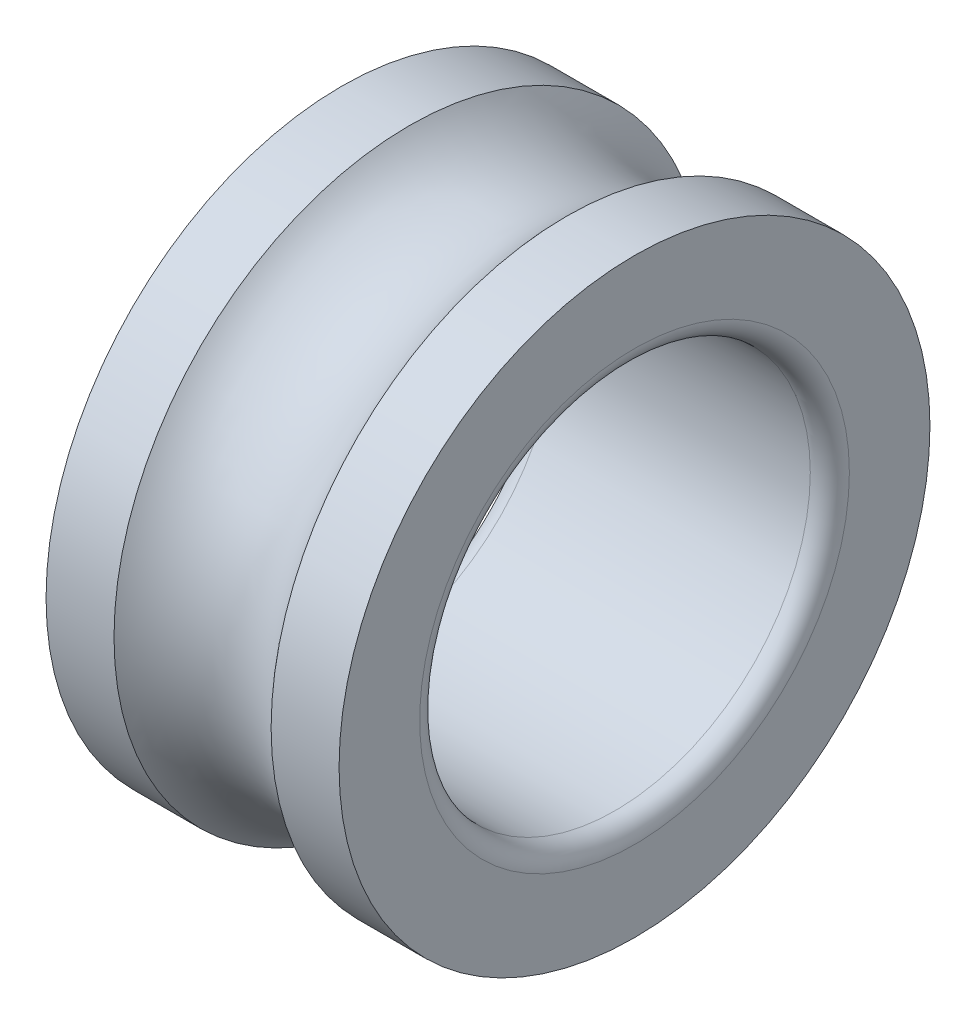
SolidWorks part; units mm, degrees
material "AISI 304"
ref_plane "Front Plane" through (0, 0, 0) normal (0, 0, 1) x (1, 0, 0)
ref_plane "Top Plane" through (0, 0, 0) normal (0, 1, 0) x (1, 0, 0)
ref_plane "Right Plane" through (0, 0, 0) normal (1, 0, 0) x (0, 0, -1)
sketch "Sketch1" plane through (0, 0, 0) normal (1, 0, 0) x (0, 0, -1)
  circle A0 centre (0, 0) radius 15.125
  circle A1 centre (0, 0) radius 10
  dimension "D1" = 30.25
  dimension "D2" = 20
extrude "Boss-Extrude1" add sketch "Sketch1" along normal mid plane 15
sketch "Sketch2" plane through (0, 0, 0) normal (0, 0, 1) x (1, 0, 0)
  line L0 (7.5, 15.125) -> (-7.5, 15.125) construction
  line L1 (0, 0) -> (19.7205, 0) construction
  circle A0 centre (0, 18.5) radius 5.25
  dimension "D1" = 10.5
  dimension "D2" = 1.875
revolve "Cut-Revolve1" cut sketch "Sketch2" angle 360 about L1
fillet "Fillet1" radius 1 2 edges at (-7.5, 0, -10) (7.5, 0, -10)
